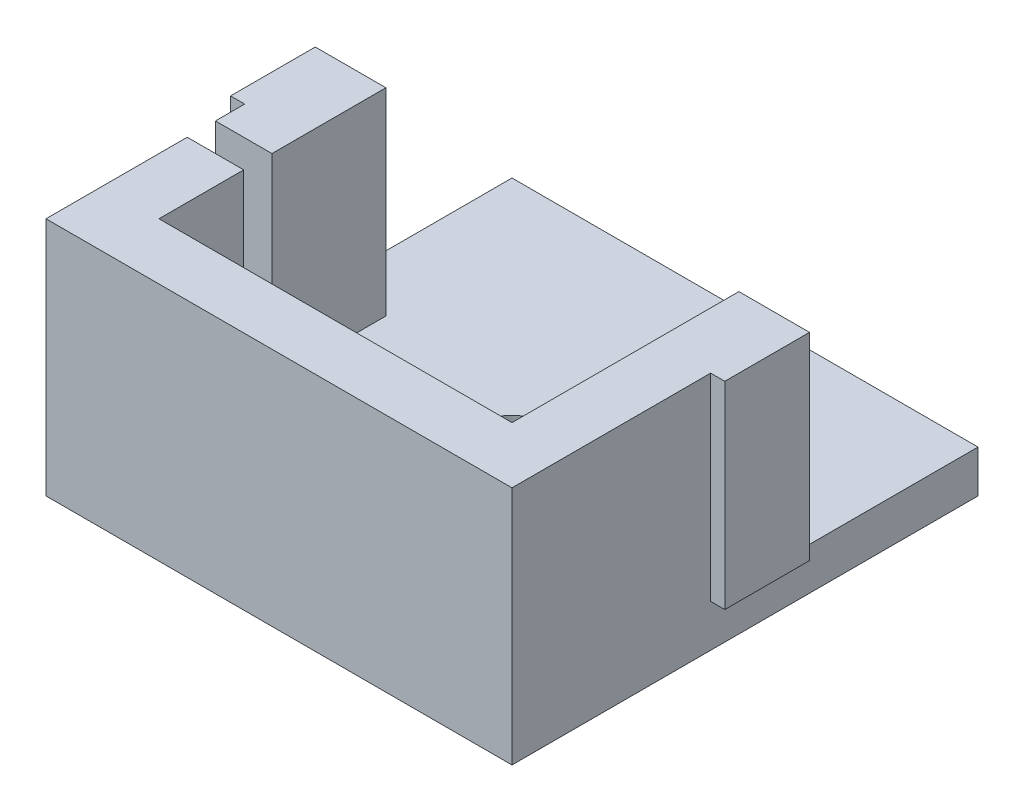
SolidWorks part; units mm, degrees
ref_plane "Front Plane" through (0, 0, 0) normal (0, 0, 1) x (1, 0, 0)
ref_plane "Top Plane" through (0, 0, 0) normal (0, 1, 0) x (1, 0, 0)
ref_plane "Right Plane" through (0, 0, 0) normal (1, 0, 0) x (0, 0, -1)
sketch "Sketch1" plane through (0, 0, 0) normal (0, 1, 0) x (1, 0, 0)
  line L1 (-18.2941, 14.8529) -> (14.7059, 14.8529)
  line L2 (-18.2941, 14.8529) -> (-18.2941, -18.1471)
  line L3 (-18.2941, -18.1471) -> (14.7059, -18.1471)
  line L4 (14.7059, 14.8529) -> (14.7059, -18.1471)
  circle A0 centre (-1.7941, -1.6471) radius 2.75
  point P6 (0, 0)
  point P7 (0, 0)
  point P8 (-18.2941, -1.6471)
  point P9 (-1.7941, 14.8529)
  dimension "D3" = 5.5
  dimension "D1" = 33
  dimension "D2" = 33
extrude "Boss-Extrude1" add sketch "Sketch1" along normal blind 17
sketch "Sketch2" plane through (0, 17, 0) normal (0, 1, 0) x (1, 0, 0)
  line L1 (-14.2941, 10.8529) -> (10.7059, 10.8529)
  line L2 (-14.2941, 10.8529) -> (-14.2941, -14.1471)
  line L3 (-14.2941, -14.1471) -> (10.7059, -14.1471)
  line L4 (10.7059, 10.8529) -> (10.7059, -14.1471)
  line L5 (-18.2941, -18.1471) -> (14.7059, -18.1471) construction
  line L6 (14.7059, -18.1471) -> (14.7059, 14.8529) construction
  dimension "D1" = 4
  dimension "D2" = 25
  dimension "D3" = 25
  dimension "D4" = 4
extrude "Cut-Extrude2" cut sketch "Sketch2" against normal blind 14
sketch "Sketch3" plane through (0, 17, 0) normal (0, 1, 0) x (1, 0, 0)
  line L0 (10.7059, -14.1471) -> (10.7059, 10.8529) construction
  line L1 (10.7059, 4.9216) -> (14.7059, 4.9216)
  line L2 (10.7059, 4.9216) -> (10.7059, 1.9216)
  line L3 (10.7059, 1.9216) -> (14.7059, 1.9216)
  line L4 (14.7059, 4.9216) -> (14.7059, 1.9216)
  line L5 (14.7059, -18.1471) -> (14.7059, 14.8529) construction
  line L6 (-1.7941, 14.8529) -> (-1.7941, -18.1471) construction
  line L7 (14.7059, 14.8529) -> (-18.2941, 14.8529) construction
  line L8 (-18.2941, -18.1471) -> (14.7059, -18.1471) construction
  line L9 (-14.2941, 1.9216) -> (-18.2941, 1.9216)
  line L10 (-18.2941, 4.9216) -> (-18.2941, 1.9216)
  line L11 (-14.2941, 4.9216) -> (-18.2941, 4.9216)
  line L12 (-14.2941, 4.9216) -> (-14.2941, 1.9216)
  dimension "D1" = 3
  dimension "D2" = 4
extrude "Cut-Extrude3" cut sketch "Sketch3" against normal blind 14
sketch "Sketch4" plane through (0, 17, 0) normal (0, 1, 0) x (1, 0, 0)
  line L0 (10.7059, 10.8529) -> (-14.2941, 10.8529) construction
  line L1 (10.7059, 10.8529) -> (-4.5217, 10.8529)
  line L2 (10.7059, 10.8529) -> (10.7059, 14.8529)
  line L3 (10.7059, 14.8529) -> (-4.5217, 14.8529)
  line L4 (-4.5217, 10.8529) -> (-4.5217, 14.8529)
  line L5 (10.7059, 10.8529) -> (-14.2941, 10.8529) construction
  line L6 (14.7059, 14.8529) -> (-18.2941, 14.8529) construction
extrude "Cut-Extrude4" cut sketch "Sketch4" against normal blind 14
sketch "Sketch5" plane through (0, 17, 0) normal (0, 1, 0) x (1, 0, 0)
  line L0 (10.7059, 4.9216) -> (10.7059, 14.8529) construction
  line L1 (10.7059, 14.8529) -> (14.7059, 14.8529)
  line L2 (10.7059, 14.8529) -> (10.7059, 4.9216)
  line L3 (10.7059, 4.9216) -> (14.7059, 4.9216)
  line L4 (14.7059, 14.8529) -> (14.7059, 4.9216)
  line L5 (10.7059, 4.9216) -> (10.7059, 14.8529) construction
  line L6 (14.7059, 4.9216) -> (10.7059, 4.9216) construction
  line L7 (14.7059, 4.9216) -> (14.7059, 14.8529) construction
extrude "Cut-Extrude5" cut sketch "Sketch5" against normal blind 14
sketch "Sketch6" plane through (0, 17, 0) normal (0, 1, 0) x (1, 0, 0)
  line L1 (-26.0367, 16.3175) -> (1.6955, 16.3175)
  line L2 (-26.0367, 16.3175) -> (-26.0367, 3.5206)
  line L3 (-26.0367, 3.5206) -> (1.6955, 3.5206)
  line L4 (1.6955, 16.3175) -> (1.6955, 3.5206)
extrude "Cut-Extrude6" cut sketch "Sketch6" against normal blind 14
sketch "Sketch7" plane through (0, 3, 0) normal (0, 1, 0) x (1, 0, 0)
  line L0 (14.7059, -18.1471) -> (14.7059, 1.9216) construction
  line L1 (14.7059, -4.0784) -> (15.7059, -4.0784)
  line L2 (14.7059, -4.0784) -> (14.7059, 1.9216)
  line L3 (14.7059, 1.9216) -> (15.7059, 1.9216)
  line L4 (15.7059, -4.0784) -> (15.7059, 1.9216)
  line L5 (10.7059, 1.9216) -> (14.7059, 1.9216) construction
  line L6 (14.7059, 14.8529) -> (-18.2941, 14.8529) construction
  line L7 (-1.7941, 14.8529) -> (-1.7941, -18.1471) construction
  line L8 (-18.2941, -18.1471) -> (14.7059, -18.1471) construction
  line L9 (-18.2941, 1.9216) -> (-19.2941, 1.9216)
  line L10 (-19.2941, -4.0784) -> (-19.2941, 1.9216)
  line L11 (-18.2941, -4.0784) -> (-19.2941, -4.0784)
  line L12 (-18.2941, -4.0784) -> (-18.2941, 1.9216)
  dimension "D1" = 6
  dimension "D2" = 1
extrude "Boss-Extrude2" add sketch "Sketch7" along normal blind 14
sketch "Sketch8" plane through (0, 17, 0) normal (0, 1, 0) x (1, 0, 0)
  line L0 (-18.2941, -4.0784) -> (-18.2941, -18.1471) construction
  line L1 (-18.2941, -6.1471) -> (-14.2941, -6.1471)
  line L2 (-18.2941, -6.1471) -> (-18.2941, -8.1471)
  line L3 (-18.2941, -8.1471) -> (-14.2941, -8.1471)
  line L4 (-14.2941, -6.1471) -> (-14.2941, -8.1471)
  line L5 (-14.2941, 1.9216) -> (-14.2941, -14.1471) construction
  line L8 (-14.2941, -14.1471) -> (10.7059, -14.1471) construction
  dimension "D1" = 2
  dimension "D2" = 6
extrude "Cut-Extrude7" cut sketch "Sketch8" against normal blind 14
